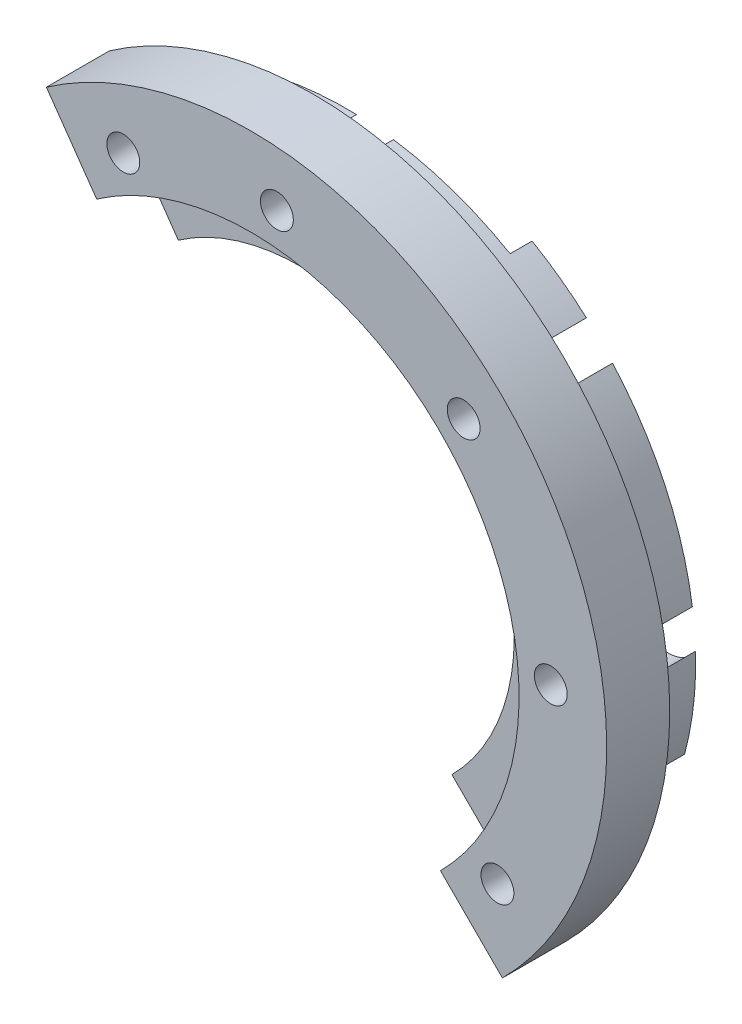
SolidWorks part; units mm, degrees
ref_plane "Front Plane" through (0, 0, 0) normal (0, 0, 1) x (1, 0, 0)
ref_plane "Top Plane" through (0, 0, 0) normal (0, 1, 0) x (1, 0, 0)
ref_plane "Right Plane" through (0, 0, 0) normal (1, 0, 0) x (0, 0, -1)
ref_plane "PZ_p24_600" through (0, 0, 24.6) normal (0, 0, 1) x (1, 0, 0)
sketch "S_prism1" plane through (0, 0, 24.6) normal (0, 0, 1) x (1, 0, 0)
  line L0 (-14.913, 21.298) -> (-11.2421, 16.0554)
  line L1 (13.8593, -13.8593) -> (18.3848, -18.3848)
  arc A0 (18.3848, -18.3848) -> (-14.913, 21.298) centre (0, 0) ccw
  arc A1 (-11.2421, 16.0554) -> (13.8593, -13.8593) centre (0, 0) cw
extrude "Boss_1" add sketch "S_prism1" along normal blind 5.6
ref_plane "PZ_p21_600" through (0, 0, 21.6) normal (0, 0, 1) x (1, 0, 0)
sketch "S_prism2" plane through (0, 0, 21.6) normal (0, 0, 1) x (1, 0, 0)
  line L0 (-13.6845, 19.5945) -> (-8.9322, 12.7897)
  line L1 (11.0443, -11.0174) -> (16.9205, -16.8792)
  arc A0 (16.9205, -16.8792) -> (-13.6845, 19.5945) centre (0, 0) ccw
  arc A1 (-8.9322, 12.7897) -> (11.0443, -11.0174) centre (0, 0) cw
extrude "Boss_2" add sketch "S_prism2" along normal blind 4.95
ref_plane "PZ_p24_500" through (0, 0, 24.5) normal (0, 0, 1) x (1, 0, 0)
sketch "S_pcut3" plane through (0, 0, 24.5) normal (0, 0, 1) x (1, 0, 0)
  line L0 (-15.4, 21.1962) -> (-14.0481, 19.3355)
  line L1 (16.6023, -17.1922) -> (18.2, -18.8467)
  arc A0 (18.2, -18.8467) -> (-15.4, 21.1962) centre (0, 0) ccw
  arc A1 (-14.0481, 19.3355) -> (16.6023, -17.1922) centre (0, 0) cw
extrude "Cut_3" cut sketch "S_pcut3" along normal blind 1.1
ref_plane "PZ_p21_500" through (0, 0, 21.5) normal (0, 0, 1) x (1, 0, 0)
sketch "S_pcut4" plane through (0, 0, 21.5) normal (0, 0, 1) x (1, 0, 0)
  line L0 (-9.9923, 13.7533) -> (-9.1107, 12.5398)
  line L1 (10.7672, -11.1498) -> (11.8092, -12.2288)
  arc A0 (11.8092, -12.2288) -> (-9.9923, 13.7533) centre (0, 0) ccw
  arc A1 (-9.1107, 12.5398) -> (10.7672, -11.1498) centre (0, 0) cw
extrude "Cut_4" cut sketch "S_pcut4" along normal blind 1.1
sketch "S_pcut5" plane through (0, 0, 21.5) normal (0, 0, 1) x (1, 0, 0)
  line L0 (-10.6977, 14.7241) -> (-9.1107, 12.5398)
  line L1 (7.75, 13.4234) -> (9.1, 15.7617)
  arc A0 (9.1, 15.7617) -> (-10.6977, 14.7241) centre (0, 0) ccw
  arc A1 (-9.1107, 12.5398) -> (7.75, 13.4234) centre (0, 0) cw
extrude "Cut_5" cut sketch "S_pcut5" along normal blind 1.1
sketch "S_pcut6" plane through (0, 0, 21.5) normal (0, 0, 1) x (1, 0, 0)
  line L0 (18.5458, -4.9693) -> (14.9719, -4.0117)
  line L1 (10.7672, -11.1498) -> (13.3374, -13.8113)
  arc A0 (13.3374, -13.8113) -> (18.5458, -4.9693) centre (0, 0) ccw
  arc A1 (14.9719, -4.0117) -> (10.7672, -11.1498) centre (0, 0) cw
extrude "Cut_6" cut sketch "S_pcut6" along normal blind 1.1
sketch "S_pcut7" plane through (0, 0, 21.5) normal (0, 0, 1) x (1, 0, 0)
  line L0 (25.3073, -6.7811) -> (19.6083, -5.254)
  line L1 (14.1016, -14.6026) -> (18.2, -18.8467)
  arc A0 (18.2, -18.8467) -> (25.3073, -6.7811) centre (0, 0) ccw
  arc A1 (19.6083, -5.254) -> (14.1016, -14.6026) centre (0, 0) cw
extrude "Cut_7" cut sketch "S_pcut7" along normal blind 1.7
sketch "S_pcut8" plane through (0, 0, 21.5) normal (0, 0, 1) x (1, 0, 0)
  line L0 (-15.4, 21.1962) -> (-11.932, 16.423)
  line L1 (10.15, 17.5803) -> (13.1, 22.6899)
  arc A0 (13.1, 22.6899) -> (-15.4, 21.1962) centre (0, 0) ccw
  arc A1 (-11.932, 16.423) -> (10.15, 17.5803) centre (0, 0) cw
extrude "Cut_8" cut sketch "S_pcut8" along normal blind 1.7
sketch "S_pcut9" plane through (0, 0, 21.5) normal (0, 0, 1) x (1, 0, 0)
  line L0 (-15.4, 21.1962) -> (-11.932, 16.423)
  line L1 (-5.254, 19.6083) -> (-6.7811, 25.3073)
  arc A0 (-6.7811, 25.3073) -> (-15.4, 21.1962) centre (0, 0) ccw
  arc A1 (-11.932, 16.423) -> (-5.254, 19.6083) centre (0, 0) cw
extrude "Cut_9" cut sketch "S_pcut9" along normal blind 1.9
sketch "S_pcut10" plane through (0, 0, 21.5) normal (0, 0, 1) x (1, 0, 0)
  line L0 (-15.4, 21.1962) -> (-12.5198, 17.2321)
  line L1 (-7.9791, 19.749) -> (-9.8147, 24.2922)
  arc A0 (-9.8147, 24.2922) -> (-15.4, 21.1962) centre (0, 0) ccw
  arc A1 (-12.5198, 17.2321) -> (-7.9791, 19.749) centre (0, 0) cw
extrude "Cut_10" cut sketch "S_pcut10" along normal blind 2.9
sketch "S_hole11" plane through (0, 0, 21.5) normal (0, 0, 1) x (1, 0, 0)
  circle A0 centre (18.0213, -12.6187) radius 1.2
  dimension "D1_S_hole11" = 2.4
  dimension "P2" = 18.0213
  dimension "P3" = 12.6187
extrude "Hole_11" cut sketch "S_hole11" along normal blind 8.8
sketch "S_hole12" plane through (0, 0, 21.5) normal (0, 0, 1) x (1, 0, 0)
  circle A0 centre (18.0213, -12.6187) radius 2.3
  dimension "D1_S_hole12" = 4.6
  dimension "P2" = 18.0213
  dimension "P3" = 12.6187
extrude "Hole_12" cut sketch "S_hole12" along normal blind 3.1
sketch "S_hole13" plane through (0, 0, 21.5) normal (0, 0, 1) x (1, 0, 0)
  circle A0 centre (21.9163, 1.9174) radius 1.2
  dimension "D1_S_hole13" = 2.4
  dimension "P2" = 21.9163
  dimension "P3" = 1.9174
extrude "Hole_13" cut sketch "S_hole13" along normal blind 8.8
sketch "S_hole14" plane through (0, 0, 21.5) normal (0, 0, 1) x (1, 0, 0)
  circle A0 centre (21.9163, 1.9174) radius 2.3
  dimension "D1_S_hole14" = 4.6
  dimension "P2" = 21.9163
  dimension "P3" = 1.9174
extrude "Hole_14" cut sketch "S_hole14" along normal blind 3.1
sketch "S_hole15" plane through (0, 0, 21.5) normal (0, 0, 1) x (1, 0, 0)
  circle A0 centre (15.5563, 15.5563) radius 1.2
  dimension "D1_S_hole15" = 2.4
  dimension "P2" = 15.5563
  dimension "P3" = 15.5563
extrude "Hole_15" cut sketch "S_hole15" along normal blind 8.8
sketch "S_hole16" plane through (0, 0, 21.5) normal (0, 0, 1) x (1, 0, 0)
  circle A0 centre (15.5563, 15.5563) radius 2.3
  dimension "D1_S_hole16" = 4.6
  dimension "P2" = 15.5563
  dimension "P3" = 15.5563
extrude "Hole_16" cut sketch "S_hole16" along normal blind 3.1
sketch "S_hole17" plane through (0, 0, 21.5) normal (0, 0, 1) x (1, 0, 0)
  circle A0 centre (1.9174, 21.9163) radius 1.2
  dimension "D1_S_hole17" = 2.4
  dimension "P2" = 1.9174
  dimension "P3" = 21.9163
extrude "Hole_17" cut sketch "S_hole17" along normal blind 8.8
sketch "S_hole18" plane through (0, 0, 21.5) normal (0, 0, 1) x (1, 0, 0)
  circle A0 centre (1.9174, 21.9163) radius 2.3
  dimension "D1_S_hole18" = 4.6
  dimension "P2" = 1.9174
  dimension "P3" = 21.9163
extrude "Hole_18" cut sketch "S_hole18" along normal blind 3.1
sketch "S_hole19" plane through (0, 0, 21.5) normal (0, 0, 1) x (1, 0, 0)
  circle A0 centre (-9.2976, 19.9388) radius 1.2
  dimension "D1_S_hole19" = 2.4
  dimension "P2" = 9.2976
  dimension "P3" = 19.9388
extrude "Hole_19" cut sketch "S_hole19" along normal blind 8.8
sketch "S_hole20" plane through (0, 0, 21.5) normal (0, 0, 1) x (1, 0, 0)
  circle A0 centre (-9.2976, 19.9388) radius 2.3
  dimension "D1_S_hole20" = 4.6
  dimension "P2" = 9.2976
  dimension "P3" = 19.9388
extrude "Hole_20" cut sketch "S_hole20" along normal blind 3.1
equation "\"plate_t\" = 3"
equation "\"clearance\" = 0.5"
